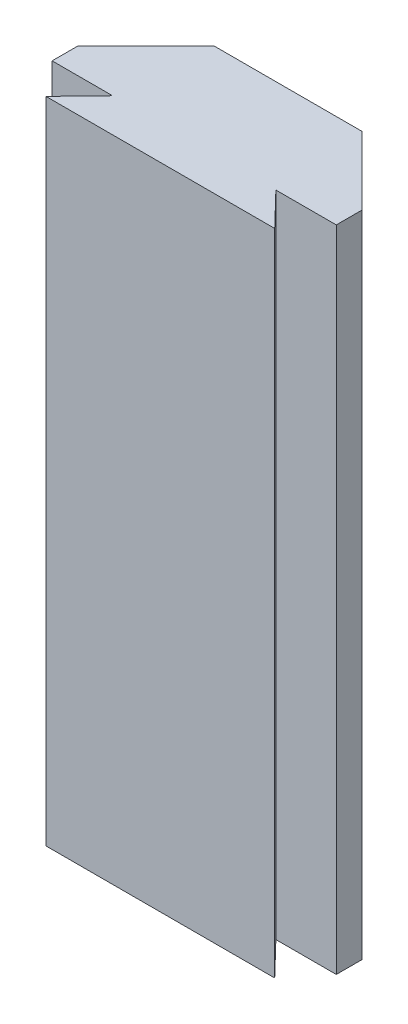
SolidWorks part; units mm, degrees
ref_plane "Front Plane" through (0, 0, 0) normal (0, 0, 1) x (1, 0, 0)
ref_plane "Top Plane" through (0, 0, 0) normal (0, 1, 0) x (1, 0, 0)
ref_plane "Right Plane" through (0, 0, 0) normal (1, 0, 0) x (0, 0, -1)
sketch "Sketch1" plane through (0, 0, 0) normal (0, 1, 0) x (1, 0, 0)
  line L0 (-2.6293, -0.3666) -> (3.1207, -0.3666)
  line L1 (3.1207, -0.3666) -> (5.7724, -3.0182)
  line L2 (-2.6293, -0.3666) -> (-5.2809, -3.0182)
  line L3 (-5.2809, -3.0182) -> (-5.2809, -4.0182)
  line L4 (5.7724, -3.0182) -> (5.7724, -4.0182)
  line L5 (-5.2809, -4.0182) -> (-2.9309, -4.0182)
  line L6 (5.7724, -4.0182) -> (3.4224, -4.0182)
  line L7 (-2.9309, -4.0182) -> (-4.2022, -5.3346)
  line L8 (3.4224, -4.0182) -> (4.6936, -5.3346)
  line L9 (-4.2022, -5.3346) -> (4.6936, -5.3346)
  point P2 (-4.906, -5.5065)
  point P11 (-4.3339, -5.3607)
  dimension "D2" = 3.75
  dimension "D3" = 3.75
  dimension "D4" = 135
  dimension "D5" = 135
  dimension "D6" = 1
  dimension "D7" = 1
  dimension "D8" = 2.35
  dimension "D9" = 2.35
  dimension "D10" = 46
  dimension "D11" = 46
  dimension "D12" = 1.83
  dimension "D13" = 1.83
  dimension "D14" = 5.75
extrude "Boss-Extrude1" add sketch "Sketch1" along normal blind 25.25
